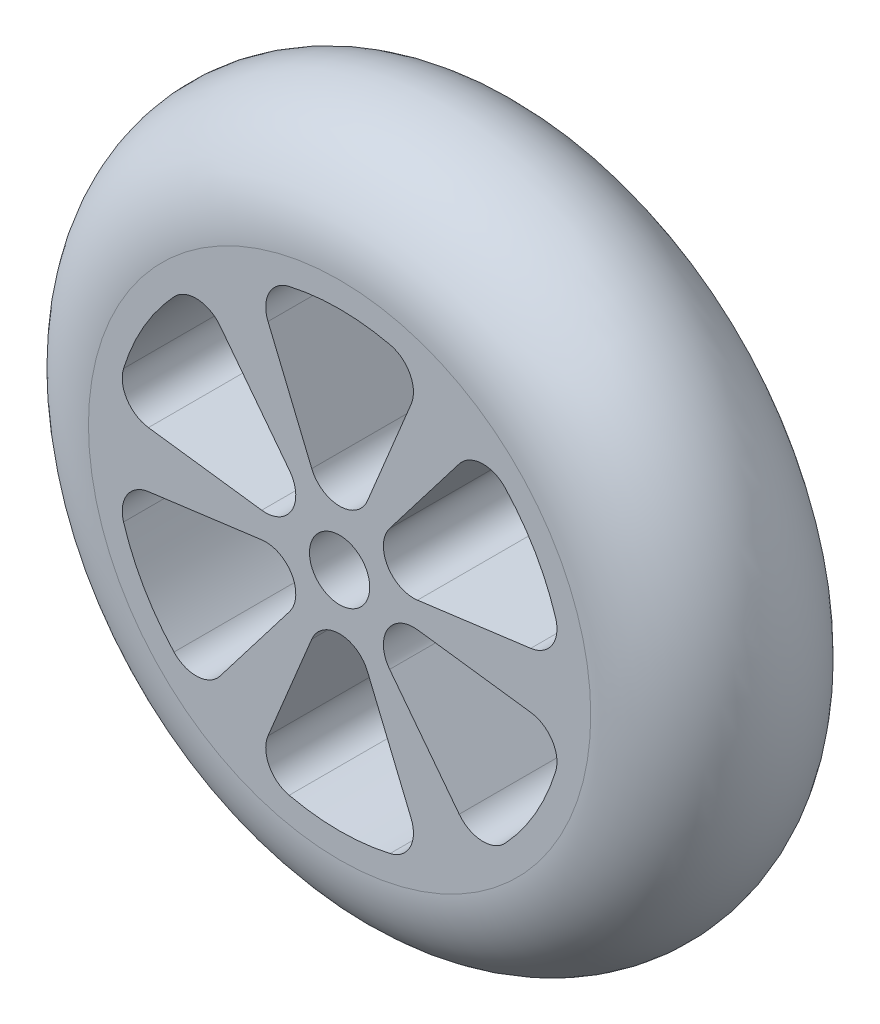
SolidWorks part; units mm, degrees
ref_plane "Front Plane" through (0, 0, 0) normal (0, 0, 1) x (1, 0, 0)
ref_plane "Top Plane" through (0, 0, 0) normal (0, 1, 0) x (1, 0, 0)
ref_plane "Right Plane" through (0, 0, 0) normal (1, 0, 0) x (0, 0, -1)
sketch "Sketch2" plane through (0, 0, 0) normal (0, 0, 1) x (1, 0, 0)
  circle A0 centre (0, 0) radius 50
  circle A1 centre (0, 0) radius 6
  dimension "D1" = 100
  dimension "D2" = 12
extrude "Boss-Extrude1" add sketch "Sketch2" along normal blind 40
sketch "Sketch1" plane through (0, 0, 40) normal (0, 0, 1) x (1, 0, 0)
  line L0 (0, 0) -> (0, -50) construction
  line L1 (-5.5433, -14.7039) -> (-14.2484, -35.72)
  line L2 (5.5433, -14.7039) -> (14.2484, -35.72)
  arc A2 (5.5433, -14.7039) -> (-5.5433, -14.7039) centre (0, -17) ccw
  arc A3 (-10.0444, -43.8647) -> (10.0444, -43.8647) centre (0, 0) ccw
  arc A4 (10.0444, -43.8647) -> (14.2484, -35.72) centre (8.7051, -38.0161) ccw
  arc A5 (-14.2484, -35.72) -> (-10.0444, -43.8647) centre (-8.7051, -38.0161) ccw
  circle A7 centre (0, 0) radius 50 construction
  circle A8 centre (0, 0) radius 6 construction
  point P1 (0, 0)
  point P3 (0, -50)
  point P9 (-16.7339, 39.181)
  point P10 (0, 50)
  point P11 (4.7722, 12.81)
  point P13 (0, 0)
  point P15 (-16.5789, 40.1166)
  point P16 (16.771, 39.1173)
  point P19 (6.9391, 14.7542)
  point P21 (-0.8793, -49.9923)
  point P22 (0, -45)
  point P23 (0, -16.981)
  point P24 (0, -25.4043)
  point P25 (0, 0)
  point P28 (0, -14.9093)
  dimension "D1" = 5
  dimension "D4" = 6
  dimension "D5" = 5
  dimension "D3" = 45
extrude "Cut-Extrude1" cut sketch "Sketch1" against normal through all
ref_axis "Axis1" through (0, 0, 40) along (0, 0, -1)
pattern_circular "CirPattern1" count 6 over 360 about axis through (0, 0, 0) along (0, 0, 1) of "Cut-Extrude1"
sketch "Sketch3" plane through (0, 0, 0) normal (0, 1, 0) x (1, 0, 0)
  line L0 (50, -40) -> (50, 0) construction
  line L1 (50, 0) -> (50, -40)
  arc A0 (50, -40) -> (50, 0) centre (50, -20) ccw
revolve "Revolve1" add sketch "Sketch3" angle 360 about axis through (0, 0, 40) along (0, 0, -1)
